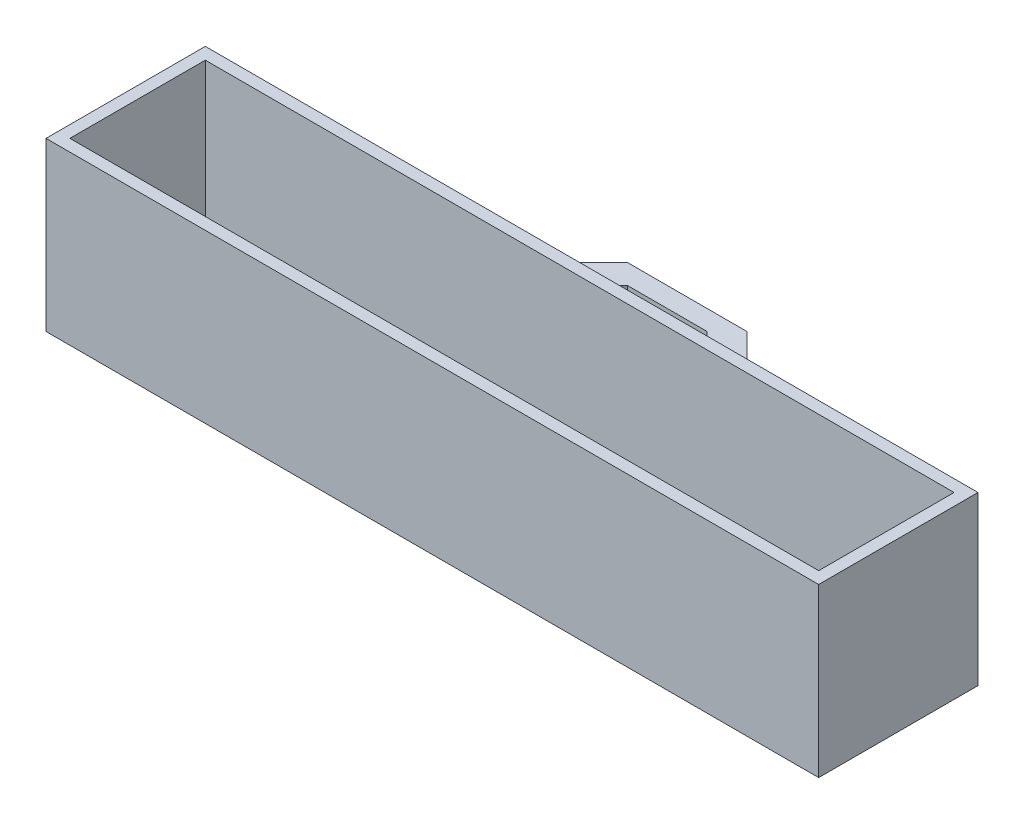
SolidWorks part; units mm, degrees
ref_plane "前视基准面" through (0, 0, 0) normal (0, 0, 1) x (1, 0, 0)
ref_plane "上视基准面" through (0, 0, 0) normal (0, 1, 0) x (1, 0, 0)
ref_plane "右视基准面" through (0, 0, 0) normal (1, 0, 0) x (0, 0, -1)
other "Configuration Table"
sketch "草图1" plane through (0, 0, 0) normal (0, 1, 0) x (1, 0, 0)
  line L0 (-470, 85) -> (-470, -85)
  line L1 (-485, 100) -> (485, 100)
  line L2 (-485, 100) -> (-485, -100)
  line L3 (-485, -100) -> (485, -100)
  line L4 (485, 100) -> (485, -100)
  line L5 (-485, 100) -> (485, -100) construction
  line L6 (-485, -100) -> (485, 100) construction
  line L7 (-470, -85) -> (470, -85)
  line L8 (470, 85) -> (470, -85)
  line L9 (-470, 85) -> (470, 85)
  point P0 (0, 0)
  dimension "D1" = 970
  dimension "D2" = 200
  dimension "D3" = 15
extrude "凸台-拉伸1" add sketch "草图1" along normal blind 200
sketch "草图2" plane through (0, 0, 0) normal (0, -1, 0) x (1, 0, 0)
  line L1 (-485, 100) -> (485, 100)
  line L2 (-485, 100) -> (-485, -100)
  line L3 (-485, -100) -> (485, -100)
  line L4 (485, 100) -> (485, -100)
extrude "凸台-拉伸2" add sketch "草图2" along normal blind 10
sketch "草图3" plane through (0, 0, -100) normal (0, 0, -1) x (-1, 0, 0)
  line L0 (-485, 200) -> (-485, -10) construction
  line L1 (-485, 95) -> (485, 95) construction
  line L2 (485, 200) -> (485, -10) construction
  line L4 (-125, 110) -> (125, 110)
  line L5 (-125, 110) -> (-125, 80)
  line L6 (-125, 80) -> (125, 80)
  line L7 (125, 110) -> (125, 80)
  line L8 (-125, 110) -> (125, 80) construction
  line L9 (-125, 80) -> (125, 110) construction
  point P8 (0, 95)
  dimension "D1" = 30
  dimension "D2" = 250
extrude "凸台-拉伸3" add sketch "草图3" along normal blind 120
sketch "草图4" plane through (0, 110, 0) normal (0, 1, 0) x (1, 0, 0)
  line L0 (485, 100) -> (-485, 100) construction
  line L1 (-100, 100) -> (100, 100)
  line L2 (-100, 100) -> (-100, 195)
  line L3 (-100, 195) -> (100, 195)
  line L4 (100, 100) -> (100, 195)
  line L5 (-125, 220) -> (125, 220) construction
  line L6 (125, 220) -> (125, 100) construction
  line L7 (-125, 220) -> (-125, 100) construction
  dimension "D1" = 25
  dimension "D2" = 25
  dimension "D3" = 25
extrude "切除-拉伸1" cut sketch "草图4" against normal blind 120
chamfer "倒角1" distance 10 angle 45 8 edges at (-100, 95, -100) (-112.5, 110, -100) (-125, 95, -100) (-112.5, 80, -100) (100, 95, -100) (112.5, 80, -100) (125, 95, -100) (112.5, 110, -100)
chamfer "倒角2" distance 50 angle 45 4 edges at (125, 95, -220) (-125, 95, -220) (-100, 95, -195) (100, 95, -195)
